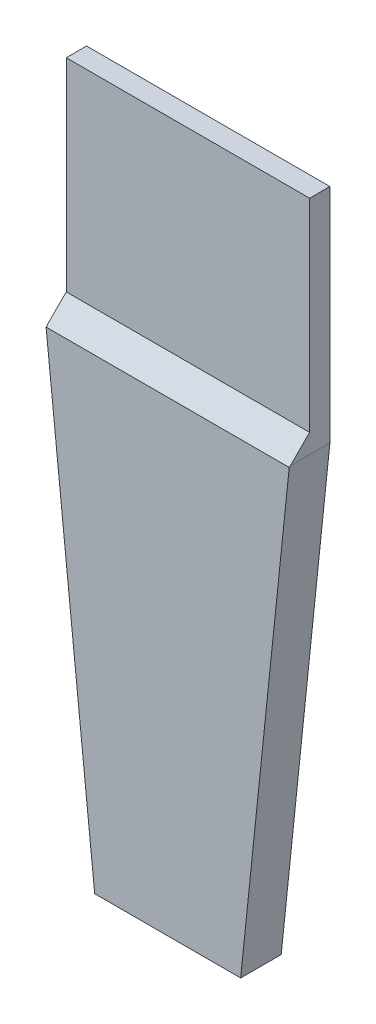
SolidWorks part; units mm, degrees
material "铜"
ref_plane "前视基准面" through (0, 0, 0) normal (0, 0, 1) x (1, 0, 0)
ref_plane "上视基准面" through (0, 0, 0) normal (0, 1, 0) x (1, 0, 0)
ref_plane "右视基准面" through (0, 0, 0) normal (1, 0, 0) x (0, 0, -1)
sketch "草图1" plane through (0, 0, 0) normal (0, 0, 1) x (1, 0, 0)
  line L12 (6, -3.2275) -> (6, 7.7205)
  line L13 (6, 7.7205) -> (-6, 7.7205)
  line L14 (-6, 7.7205) -> (-6, -3.2275)
  line L15 (-6, -3.2275) -> (-3.5988, -26.2795)
  line L16 (-3.5988, -26.2795) -> (3.5988, -26.2795)
  line L17 (3.5988, -26.2795) -> (6, -3.2275)
extrude "凸台-拉伸1" add sketch "草图1" along normal blind 1
sketch "草图2" plane through (0, 0, 0) normal (1, 0, 0) x (0, 0, -1)
  line L0 (-2, -26.2795) -> (-1, -26.2795)
  line L2 (-1, -26.2795) -> (-1, -2.2795)
  line L3 (-1, -2.2795) -> (-2, -3.2795)
  line L4 (-2, -3.2795) -> (-2, -26.2795)
  dimension "D1" = 1
  dimension "D2" = 23
  dimension "D3" = 45
extrude "凸台-拉伸2" add sketch "草图2" along normal mid plane 12
sketch "草图3" plane through (0, 0, 1) normal (0, 0, -1) x (-1, 0, 0)
  line L3 (6, -26.2795) -> (6, -3.2275)
  line L4 (6, -3.2275) -> (3.5988, -26.2795)
  line L5 (3.5988, -26.2795) -> (6, -26.2795)
  line L6 (6, -26.2795) -> (6, -3.2275)
  line L7 (6, -3.2275) -> (3.5988, -26.2795)
  line L8 (3.5988, -26.2795) -> (6, -26.2795)
  line L9 (-6, -26.2795) -> (-3.5988, -26.2795)
  line L10 (-3.5988, -26.2795) -> (-6, -3.2275)
  line L11 (-6, -3.2275) -> (-6, -26.2795)
  line L12 (-6, -26.2795) -> (-3.5988, -26.2795)
  line L13 (-3.5988, -26.2795) -> (-6, -3.2275)
  line L14 (-6, -3.2275) -> (-6, -26.2795)
  dimension "D1" = 0
  dimension "D2" = 0
extrude "切除-拉伸1" cut sketch "草图3" against normal through all
